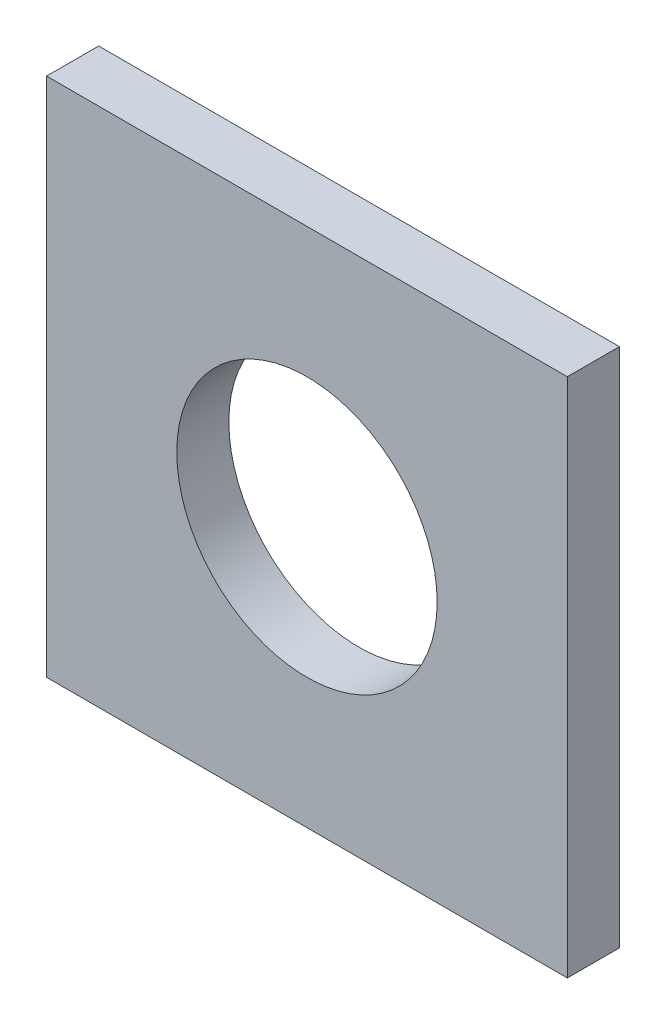
SolidWorks part; units mm, degrees
ref_plane "Front Plane" through (0, 0, 0) normal (0, 0, 1) x (1, 0, 0)
ref_plane "Top Plane" through (0, 0, 0) normal (0, 1, 0) x (1, 0, 0)
ref_plane "Right Plane" through (0, 0, 0) normal (1, 0, 0) x (0, 0, -1)
sketch "Sketch1" plane through (0, 0, 0) normal (0, 0, 1) x (1, 0, 0)
  line L1 (-50, -50) -> (50, -50)
  line L2 (-50, -50) -> (-50, 50)
  line L3 (-50, 50) -> (50, 50)
  line L4 (50, -50) -> (50, 50)
  line L5 (-50, -50) -> (50, 50) construction
  line L6 (-50, 50) -> (50, -50) construction
  point P0 (0, 0)
  dimension "D1" = 100
  dimension "D2" = 100
extrude "Boss-Extrude1" add sketch "Sketch1" along normal blind 10
sketch "Sketch2" plane through (0, 0, 10) normal (0, 0, 1) x (1, 0, 0)
  circle A0 centre (0, 0) radius 25
  dimension "D1" = 50
extrude "Cut-Extrude1" cut sketch "Sketch2" against normal blind 10
